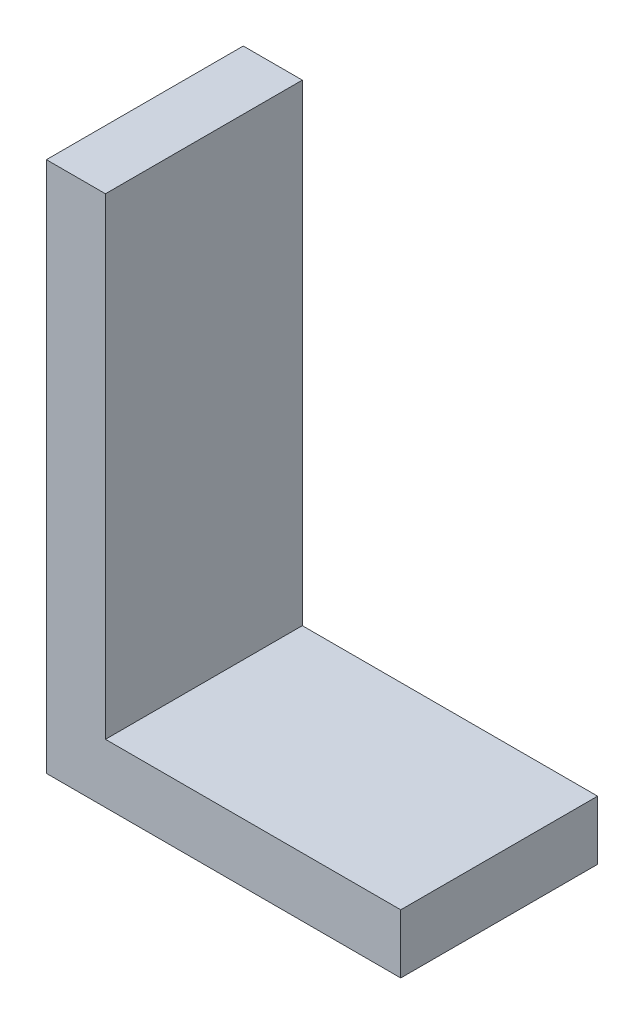
SolidWorks part; units mm, degrees
ref_plane "Front Plane" through (0, 0, 0) normal (0, 0, 1) x (1, 0, 0)
ref_plane "Top Plane" through (0, 0, 0) normal (0, 1, 0) x (1, 0, 0)
ref_plane "Right Plane" through (0, 0, 0) normal (1, 0, 0) x (0, 0, -1)
sketch "Sketch1" plane through (0, 0, 0) normal (0, 0, 1) x (1, 0, 0)
  line L0 (0, 0) -> (0, -27)
  line L1 (0, -27) -> (18, -27)
  line L2 (18, -27) -> (18, -24)
  line L3 (18, -24) -> (3, -24)
  line L4 (3, -24) -> (3, 0)
  line L5 (3, 0) -> (0, 0)
  dimension "D1" = 27
  dimension "D2" = 3
  dimension "D3" = 3
  dimension "D4" = 18
extrude "Boss-Extrude1" add sketch "Sketch1" along normal blind 10
